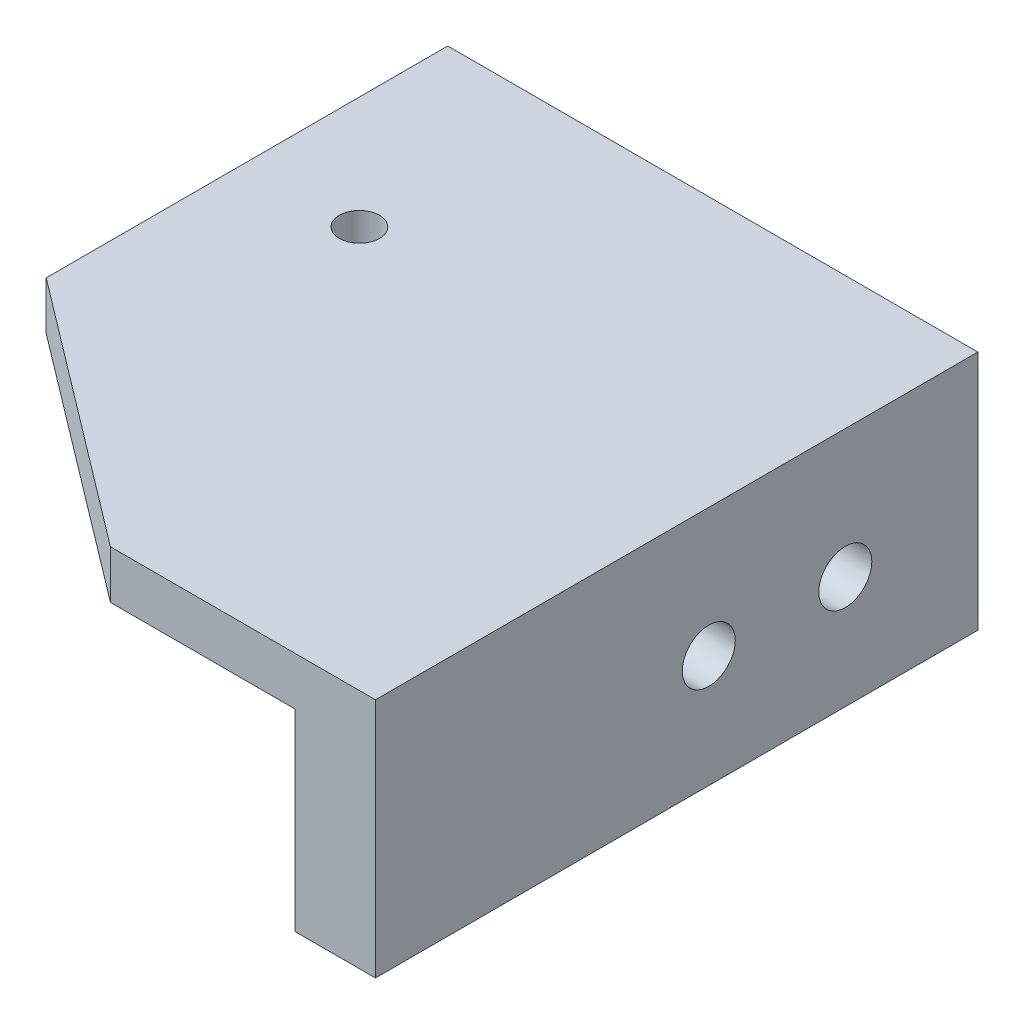
SolidWorks part; units mm, degrees
ref_plane "Front Plane" through (0, 0, 0) normal (0, 0, 1) x (1, 0, 0)
ref_plane "Top Plane" through (0, 0, 0) normal (0, 1, 0) x (1, 0, 0)
ref_plane "Right Plane" through (0, 0, 0) normal (1, 0, 0) x (0, 0, -1)
sketch "Skizze1" plane through (0, 0, 0) normal (0, 0, 1) x (1, 0, 0)
  line L1 (-16.5, 7.5) -> (16.5, 7.5)
  line L2 (-16.5, 7.5) -> (-16.5, -7.5)
  line L3 (-16.5, -7.5) -> (16.5, -7.5)
  line L4 (16.5, 7.5) -> (16.5, -7.5)
  line L5 (0, -7.5) -> (0, 7.5) construction
  line L6 (-16.5, 0) -> (16.5, 0) construction
  point P76 (0, 0)
  dimension "D1" = 33
  dimension "D2" = 15
extrude "Aufsatz-Linear austragen1" add sketch "Skizze1" along normal blind 25 and the other way blind 12.5
sketch "Skizze2" plane through (0, 0, 25) normal (0, 0, 1) x (1, 0, 0)
  line L0 (16.5, 7.5) -> (-16.5, 7.5) construction
  line L1 (-16.5, -7.5) -> (11.5, -7.5)
  line L2 (-16.5, -7.5) -> (-16.5, 4.5)
  line L3 (-16.5, 4.5) -> (11.5, 4.5)
  line L4 (11.5, -7.5) -> (11.5, 4.5)
  line L5 (-2.5, 4.5) -> (-2.5, -7.5) construction
  line L6 (-16.5, -1.5) -> (11.5, -1.5) construction
  line L7 (16.5, -7.5) -> (16.5, 7.5) construction
  point P128 (-2.5, -1.5)
  dimension "D1" = 3
  dimension "D2" = 5
extrude "Schnitt-Linear austragen1" cut sketch "Skizze2" against normal through all
hole_wizard "M3 Gewindebohrung1" positions "Skizze3" profile "Skizze4" tap size "M3" standard "DIN" end condition up to next
sketch "Skizze3" plane through (0, 7.5, 0) normal (0, 1, 0) x (1, 0, 0)
  line L2 (16.5, -25) -> (16.5, 12.5) construction
  point P0 (-9.5, 0)
  dimension "D1" = 26
sketch "Skizze4" plane through (-9.5, 7.5, 0) normal (1, 0, 0) x (0, 0, 1)
  line L0 (0, 0) -> (0, 3)
  line L1 (0, 3) -> (1.25, 3)
  line L2 (1.25, 3) -> (1.25, 0)
  line L5 (1.25, 0) -> (0, 0)
  line L11 (0, -6.35) -> (0, 107.95) construction
  dimension "Bohrerdurchmesser" = 2.5
  dimension "Bohrungstiefe" = 3
cosmetic thread "Bohrungsgewinde1" parameters "D2"=3
hole_wizard "M4 Gewindebohrung1" positions "Skizze5" profile "Skizze6" tap size "M4" standard "DIN" end condition up to next
sketch "Skizze5" plane through (16.5, 0, 0) normal (1, 0, 0) x (0, 0, -1)
  line L1 (-25, 7.5) -> (12.5, 7.5) construction
  line L3 (0, 0) -> (0, -7.5) construction
  line L4 (12.5, -7.5) -> (-25, -7.5) construction
  point P0 (-4.25, -0.5)
  point P2 (4.25, -0.5)
  dimension "D1" = 8.5
  dimension "D2" = 8
sketch "Skizze6" plane through (16.5, -0.5, 4.25) normal (0, 1, 0) x (0, 0, -1)
  line L0 (0, 0) -> (0, 5)
  line L1 (0, 5) -> (1.65, 5)
  line L2 (1.65, 5) -> (1.65, 0)
  line L5 (1.65, 0) -> (0, 0)
  line L11 (0, -6.35) -> (0, 107.95) construction
  dimension "Bohrerdurchmesser" = 3.3
  dimension "Bohrungstiefe" = 5
cosmetic thread "Bohrungsgewinde2" parameters "D2"=4
cosmetic thread "Bohrungsgewinde3" parameters "D2"=4
sketch "Skizze7" plane through (0, 7.5, 0) normal (0, 1, 0) x (1, 0, 0)
  line L0 (0, -25) -> (-16.5, -12.5)
  line L1 (16.5, -25) -> (-16.5, -25) construction
  line L2 (-16.5, 12.5) -> (-16.5, -25) construction
  line L3 (16.5, 12.5) -> (-16.5, 12.5) construction
  line L4 (0, -25) -> (-16.5, -25)
  line L5 (-16.5, -25) -> (-16.5, -12.5)
  dimension "D1" = 25
extrude "Schnitt-Linear austragen2" cut sketch "Skizze7" against normal through all
